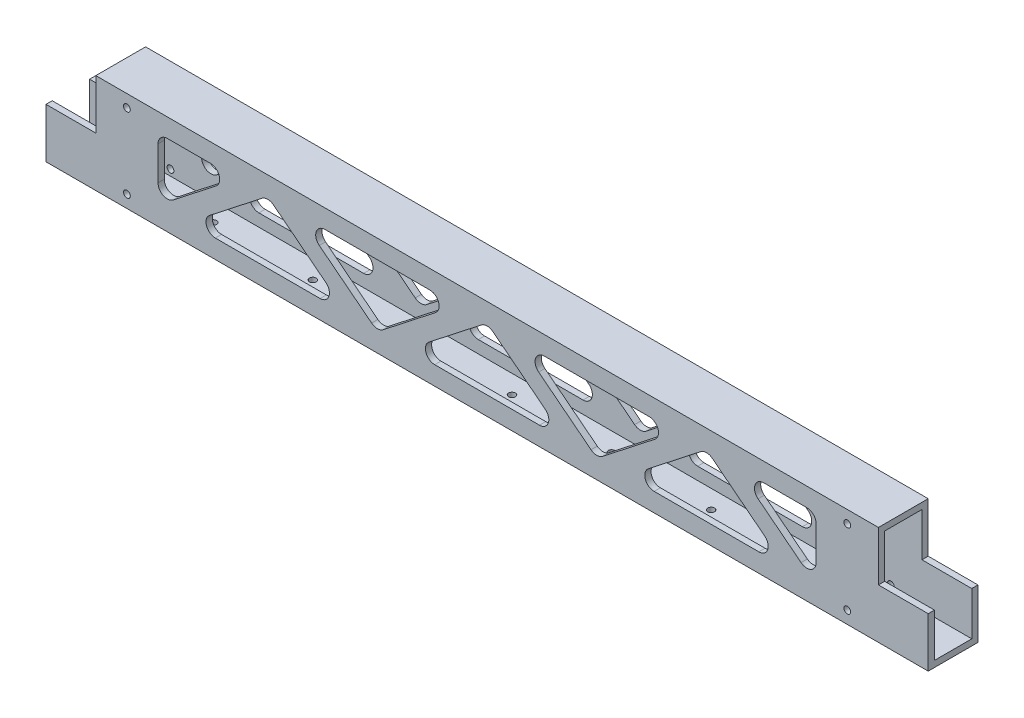
SolidWorks part; units mm, degrees
material "6061-T6 (SS)"
ref_plane "Front Plane" through (0, 0, 0) normal (0, 0, 1) x (1, 0, 0)
ref_plane "Top Plane" through (0, 0, 0) normal (0, 1, 0) x (1, 0, 0)
ref_plane "Right Plane" through (0, 0, 0) normal (1, 0, 0) x (0, 0, -1)
sketch "Sketch1" plane through (0, 0, 0) normal (1, 0, 0) x (0, 0, -1)
  line L0 (9.525, 22.225) -> (9.525, 25.4) construction
  line L1 (-12.7, -25.4) -> (12.7, -25.4)
  line L2 (-12.7, -25.4) -> (-12.7, 25.4)
  line L3 (-12.7, 25.4) -> (12.7, 25.4)
  line L4 (12.7, -25.4) -> (12.7, 25.4)
  line L5 (-12.7, -25.4) -> (12.7, 25.4) construction
  line L6 (-12.7, 25.4) -> (12.7, -25.4) construction
  line L7 (-9.525, -22.225) -> (9.525, -22.225)
  line L8 (-9.525, -22.225) -> (-9.525, 22.225)
  line L9 (-9.525, 22.225) -> (9.525, 22.225)
  line L10 (9.525, -22.225) -> (9.525, 22.225)
  line L11 (-9.525, -22.225) -> (9.525, 22.225) construction
  line L12 (-9.525, 22.225) -> (9.525, -22.225) construction
  line L13 (9.525, 22.225) -> (12.7, 22.225) construction
  point P0 (0, 0)
  point P6 (0, 0)
  dimension "D1" = 25.4
  dimension "D2" = 50.8
  dimension "D3" = 3.175
extrude "Boss-Extrude1" add sketch "Sketch1" along normal mid plane 450.0499
sketch "Sketch2" plane through (0, 0, 12.7) normal (0, 0, 1) x (1, 0, 0)
  line L1 (-225.0249, 25.4) -> (-199.6249, 25.4)
  line L2 (-225.0249, 25.4) -> (-225.0249, 0)
  line L3 (-225.0249, 0) -> (-199.6249, 0)
  line L4 (-199.6249, 25.4) -> (-199.6249, 0)
  line L5 (225.0249, 25.4) -> (199.6249, 25.4)
  line L6 (225.0249, 25.4) -> (225.0249, 0)
  line L7 (225.0249, 0) -> (199.6249, 0)
  line L8 (199.6249, 25.4) -> (199.6249, 0)
  dimension "D1" = 25.4
extrude "Cut-Extrude1" cut sketch "Sketch2" against normal through all
hole_wizard "#8-32 Tapped Hole1" positions "Sketch4" profile "Sketch3" tap size "#8-32" standard "ANSI Inch" end condition through all
sketch "Sketch4" plane through (0, 0, 12.7) normal (0, 0, 1) x (1, 0, 0)
  line L0 (0, 0) -> (0, 50000) construction
  line L1 (0, 0) -> (-50000, 0) construction
  line L2 (-225.0249, 0) -> (-225.0249, -25.4) construction
  point P0 (-183.7499, 19.05)
  point P2 (-183.7499, -19.05)
  point P4 (183.7499, 19.05)
  point P6 (183.7499, -19.05)
  dimension "D1" = 41.275
  dimension "D2" = 38.1
sketch "Sketch3" plane through (-183.7499, 19.05, 12.7) normal (1, 0, 0) x (0, -1, 0)
  line L0 (0, 0) -> (0, 25.4)
  line L1 (0, 25.4) -> (1.7272, 25.4)
  line L2 (1.7272, 25.4) -> (1.7272, 0)
  line L5 (1.7272, 0) -> (0, 0)
  line L11 (0, -6.35) -> (0, 107.95) construction
  dimension "Thru Tap Drill Dia." = 3.4544
  dimension "Thru Tap Drill Depth" = 25.4
cosmetic thread "Hole Thread1" parameters "D2"=4.1656
cosmetic thread "Hole Thread2" parameters "D2"=4.1656
cosmetic thread "Hole Thread3" parameters "D2"=4.1656
cosmetic thread "Hole Thread4" parameters "D2"=4.1656
hole_wizard "#8-32 Tapped Hole2" positions "Sketch6" profile "Sketch5" tap size "#8-32" standard "ANSI Inch"
sketch "Sketch6" plane through (0, -25.4, 0) normal (0, -1, 0) x (-1, 0, 0)
  line L0 (-152.4, 0) -> (-101.6, 0) construction
  line L1 (-101.6, 0) -> (-50.8, 0) construction
  line L2 (-50.8, 0) -> (0, 0) construction
  line L3 (0, 0) -> (50.8, 0) construction
  line L4 (50.8, 0) -> (101.6, 0) construction
  line L5 (101.6, 0) -> (152.4, 0) construction
  point P0 (0, 0)
  point P3 (50.8, 0)
  point P5 (101.6, 0)
  point P7 (152.4, 0)
  point P9 (-50.8, 0)
  point P11 (-101.6, 0)
  point P13 (-152.4, 0)
  dimension "D1" = 50.8
cosmetic thread "Hole Thread5" parameters "D2"=4.1656
cosmetic thread "Hole Thread6" parameters "D2"=4.1656
cosmetic thread "Hole Thread7" parameters "D2"=4.1656
cosmetic thread "Hole Thread8" parameters "D2"=4.1656
cosmetic thread "Hole Thread9" parameters "D2"=4.1656
cosmetic thread "Hole Thread10" parameters "D2"=4.1656
cosmetic thread "Hole Thread11" parameters "D2"=4.1656
sketch "Sketch5" plane through (0, -25.4, 0) normal (1, 0, 0) x (0, 0, -1)
  line L0 (0, 0) -> (0, 3.175)
  line L1 (0, 3.175) -> (1.7272, 3.175)
  line L2 (1.7272, 3.175) -> (1.7272, 0)
  line L5 (1.7272, 0) -> (0, 0)
  line L11 (0, -6.35) -> (0, 107.95) construction
  dimension "Thru Tap Drill Dia." = 3.4544
  dimension "Thru Tap Drill Depth" = 3.175
sketch "Sketch7" plane through (0, 0, 12.7) normal (0, 0, 1) x (1, 0, 0)
  line L0 (-167.8749, -0.8408) -> (-167.8749, 49999.1592) construction
  line L1 (167.8749, 0.8408) -> (167.8749, 50000.8408) construction
  line L2 (0, 0) -> (0, 50000) construction
  line L3 (-225.0249, 0) -> (-225.0249, -25.4) construction
  line L4 (-96.4743, 15.875) -> (-127.3589, 15.875) construction
  line L5 (15.4423, 15.875) -> (-15.4423, 15.875) construction
  line L40 (-167.8749, 15.875) -> (-167.8749, -15.875)
  line L41 (-167.8749, -15.875) -> (-127.3589, 15.875)
  line L42 (-127.3589, 15.875) -> (-167.8749, 15.875)
  line L43 (-111.9166, 15.875) -> (-152.4326, -15.875)
  line L44 (-152.4326, -15.875) -> (-71.4006, -15.875)
  line L45 (-71.4006, -15.875) -> (-111.9166, 15.875)
  line L47 (-96.4743, 15.875) -> (-55.9583, -15.875)
  line L48 (190.0999, -9.525) -> (190.0999, 15.875)
  line L49 (215.4999, -9.525) -> (190.0999, -9.525)
  line L50 (215.4999, -15.875) -> (215.4999, -9.525)
  line L51 (-215.4999, -15.875) -> (215.4999, -15.875)
  line L52 (-215.4999, -9.525) -> (-215.4999, -15.875)
  line L53 (-190.0999, -9.525) -> (-215.4999, -9.525)
  line L54 (-190.0999, 15.875) -> (-190.0999, -9.525)
  line L55 (190.0999, 15.875) -> (-190.0999, 15.875)
  line L56 (190.0999, -9.525) -> (190.0999, 15.875) construction
  line L57 (215.4999, -9.525) -> (190.0999, -9.525) construction
  line L58 (215.4999, -15.875) -> (215.4999, -9.525) construction
  line L59 (-215.4999, -15.875) -> (215.4999, -15.875) construction
  line L60 (-215.4999, -9.525) -> (-215.4999, -15.875) construction
  line L61 (-190.0999, -9.525) -> (-215.4999, -9.525) construction
  line L62 (-190.0999, 15.875) -> (-190.0999, -9.525) construction
  line L63 (190.0999, 15.875) -> (-190.0999, 15.875) construction
  line L64 (-55.9583, -15.875) -> (-15.4423, 15.875)
  line L65 (-15.4423, 15.875) -> (-96.4743, 15.875)
  line L66 (0, 15.875) -> (-40.516, -15.875)
  line L67 (-40.516, -15.875) -> (40.516, -15.875)
  line L68 (40.516, -15.875) -> (0, 15.875)
  line L69 (15.4423, 15.875) -> (55.9583, -15.875)
  line L70 (55.9583, -15.875) -> (96.4743, 15.875)
  line L71 (96.4743, 15.875) -> (15.4423, 15.875)
  line L72 (111.9166, 15.875) -> (71.4006, -15.875)
  line L73 (71.4006, -15.875) -> (152.4326, -15.875)
  line L74 (152.4326, -15.875) -> (111.9166, 15.875)
  line L75 (167.8749, 15.875) -> (167.8749, -15.875)
  line L76 (167.8749, -15.875) -> (127.3589, 15.875)
  line L77 (127.3589, 15.875) -> (167.8749, 15.875)
  dimension "D1" = 57.15
  dimension "D3" = 9.525
  dimension "D2" = 9.525
extrude "Cut-Extrude2" cut sketch "Sketch7" against normal through all
fillet "Fillet1" radius 4.7625 42 edges at (-127.3589, 15.875, 11.1125) (-167.8749, -15.875, 11.1125) (-167.8749, 15.875, 11.1125) (-71.4006, -15.875, 11.1125) (-152.4326, -15.875, 11.1125) (40.516, -15.875, 11.1125) (-40.516, -15.875, 11.1125) (0, 15.875, 11.1125) (-15.4423, 15.875, 11.1125) (-55.9583, -15.875, 11.1125) (-96.4743, 15.875, 11.1125) (96.4743, 15.875, 11.1125) (55.9583, -15.875, 11.1125) (15.4423, 15.875, 11.1125) (152.4326, -15.875, 11.1125) (71.4006, -15.875, 11.1125) (111.9166, 15.875, 11.1125) (167.8749, 15.875, 11.1125) (167.8749, -15.875, 11.1125) (127.3589, 15.875, 11.1125) (-111.9166, 15.875, 11.1125) (-167.8749, -15.875, -11.1125) (-127.3589, 15.875, -11.1125) (-152.4326, -15.875, -11.1125) (-111.9166, 15.875, -11.1125) (-71.4006, -15.875, -11.1125) (-40.516, -15.875, -11.1125) (0, 15.875, -11.1125) (40.516, -15.875, -11.1125) (-55.9583, -15.875, -11.1125) (-96.4743, 15.875, -11.1125) (-15.4423, 15.875, -11.1125) (55.9583, -15.875, -11.1125) (15.4423, 15.875, -11.1125) (96.4743, 15.875, -11.1125) (71.4006, -15.875, -11.1125) (111.9166, 15.875, -11.1125) (152.4326, -15.875, -11.1125) (167.8749, -15.875, -11.1125) (127.3589, 15.875, -11.1125) (167.8749, 15.875, -11.1125) (-167.8749, 15.875, -11.1125)
